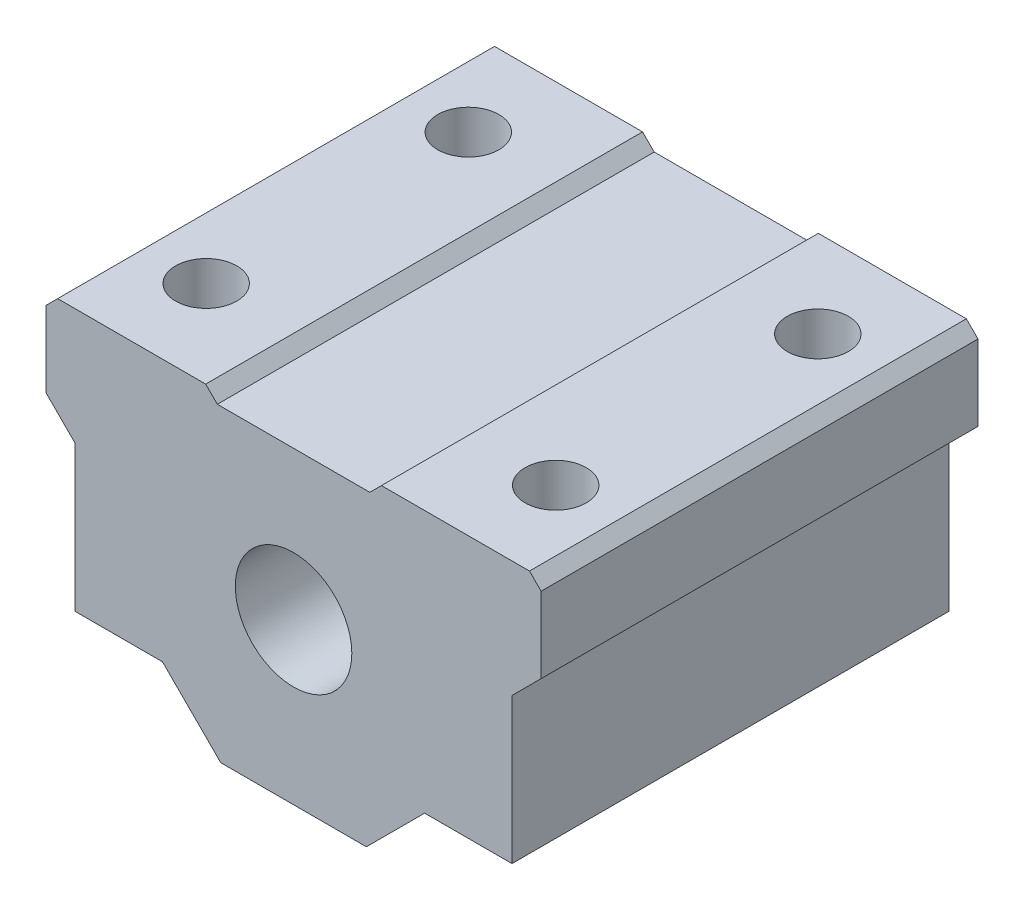
SolidWorks part; units mm, degrees
ref_plane "前视基准面" through (0, 0, 0) normal (0, 0, 1) x (1, 0, 0)
ref_plane "上视基准面" through (0, 0, 0) normal (0, 1, 0) x (1, 0, 0)
ref_plane "右视基准面" through (0, 0, 0) normal (1, 0, 0) x (0, 0, -1)
sketch "草图1" plane through (0, 0, 0) normal (0, 0, 1) x (1, 0, 0)
  line L0 (0, 17.1569) -> (0, 10.2) construction
  line L11 (5, -11) -> (-5, -11)
  line L12 (-5, -11) -> (-9, -7)
  line L13 (-9, -7) -> (-15, -7)
  line L14 (-15, -7) -> (-15, 3)
  line L15 (-15, 3) -> (-17, 5)
  line L16 (-17, 5) -> (-17, 10.2)
  line L17 (-17, 10.2) -> (-16.2, 11)
  line L18 (-6.035, 11) -> (-5.235, 10.2)
  line L19 (-5.235, 10.2) -> (5.235, 10.2)
  line L20 (-16.2, 11) -> (-6.035, 11)
  line L23 (0, -11) -> (0, -12.7265) construction
  line L24 (16.2, 11) -> (6.035, 11)
  line L25 (6.035, 11) -> (5.235, 10.2)
  line L26 (17, 10.2) -> (16.2, 11)
  line L27 (17, 5) -> (17, 10.2)
  line L28 (15, 3) -> (17, 5)
  line L29 (15, -7) -> (15, 3)
  line L30 (9, -7) -> (15, -7)
  line L31 (5, -11) -> (9, -7)
  circle A0 centre (0, 0) radius 4
  point P18 (0, 0)
  point P19 (0, -3.5234)
  point P20 (-5.4102, 12.9578)
  point P21 (0, 0)
  dimension "D11" = 4
  dimension "D1" = 34
  dimension "D2" = 22
  dimension "D3" = 18
  dimension "D4" = 6
  dimension "D5" = 11
  dimension "D6" = 0.8
  dimension "D7" = 45
  dimension "D8" = 45
  dimension "D9" = 45
  dimension "D10" = 10
  dimension "D12" = 45
  dimension "D13" = 2
extrude "凸台-拉伸1" add sketch "草图1" along normal blind 30
sketch "草图2" plane through (0, 11, 0) normal (0, 1, 0) x (1, 0, 0)
  line L0 (-17, -30) -> (-17, 0) construction
  line L1 (-6.035, 0) -> (-16.2, 0) construction
  line L3 (0, 0) -> (0, -32.5661) construction
  circle A0 centre (-12, -6) radius 2.1
  circle A1 centre (-12, -24) radius 2.1
  circle A2 centre (12, -6) radius 2.1
  circle A3 centre (12, -24) radius 2.1
  dimension "D1" = 4.2
  dimension "D2" = 5
  dimension "D3" = 6
  dimension "D4" = 4.2
  dimension "D5" = 18
extrude "切除-拉伸1" cut sketch "草图2" against normal blind 30
